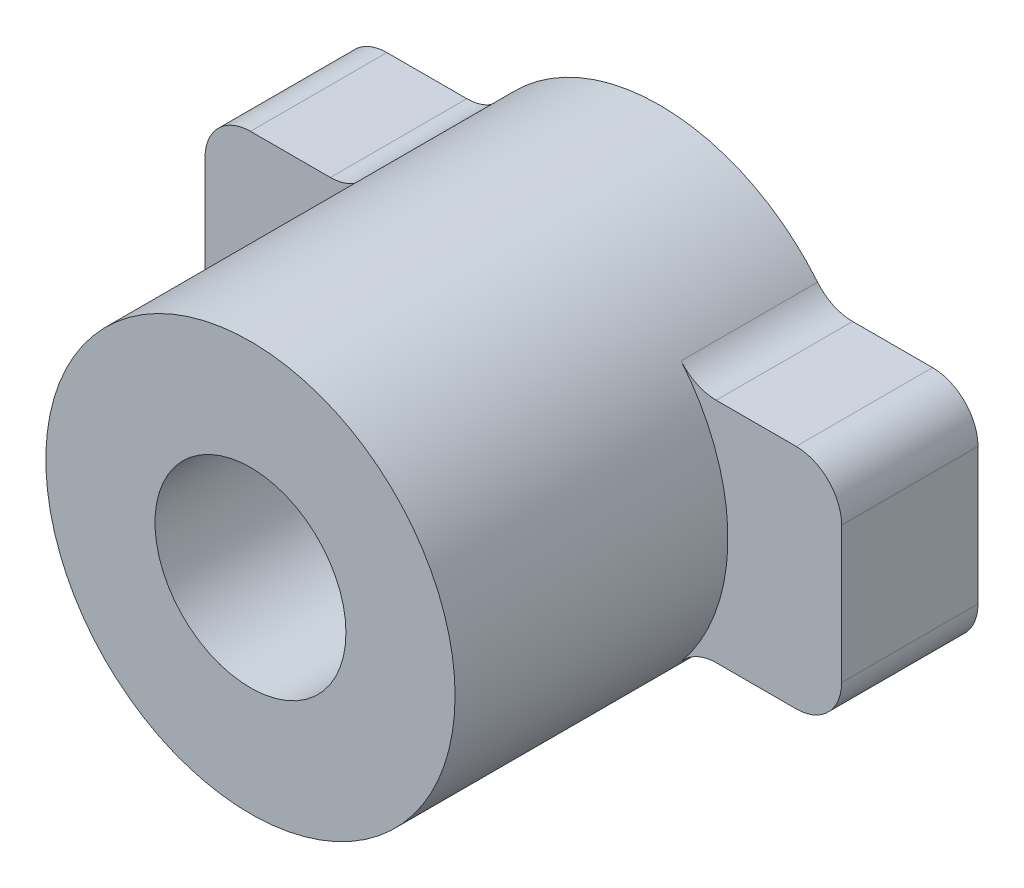
SolidWorks part; units mm, degrees
material "6061 合金"
ref_plane "前视基准面" through (0, 0, 0) normal (0, 0, 1) x (1, 0, 0)
ref_plane "上视基准面" through (0, 0, 0) normal (0, 1, 0) x (1, 0, 0)
ref_plane "右视基准面" through (0, 0, 0) normal (1, 0, 0) x (0, 0, -1)
sketch "草图1" plane through (0, 0, 0) normal (0, 0, 1) x (1, 0, 0)
  circle A0 centre (0, 0) radius 4.5
  dimension "D1" = 9
extrude "凸台-拉伸1" add sketch "草图1" along normal blind 9
sketch "草图2" plane through (0, 0, 0) normal (0, 0, -1) x (-1, 0, 0)
  line L1 (-7, -2.5) -> (7, -2.5)
  line L2 (-7, -2.5) -> (-7, 2.5)
  line L3 (-7, 2.5) -> (7, 2.5)
  line L4 (7, -2.5) -> (7, 2.5)
  line L5 (0, 2.5) -> (0, -2.5) construction
  line L6 (-7, 0) -> (7, 0) construction
  point P0 (0, 0)
  dimension "D1" = 14
  dimension "D2" = 5
extrude "凸台-拉伸2" add sketch "草图2" against normal blind 3
hole_wizard "M5 螺纹孔1" positions "草图3" profile "草图4" tap size "M5" standard "GB" end condition up to next
sketch "草图3" plane through (0, 0, 9) normal (0, 0, 1) x (1, 0, 0)
  point P0 (0, 0)
sketch "草图4" plane through (0, 0, 9) normal (1, 0, 0) x (0, -1, 0)
  line L0 (0, 0) -> (0, 9)
  line L1 (0, 9) -> (2.1, 9)
  line L2 (2.1, 9) -> (2.1, 0)
  line L5 (2.1, 0) -> (0, 0)
  line L11 (0, -6.35) -> (0, 107.95) construction
  dimension "通孔螺纹孔钻头直径" = 4.2
  dimension "通孔螺纹孔钻头深度" = 9
cosmetic thread "孔螺蚊线1"
fillet "圆角1" radius 1 8 edges at (3.7417, 2.5, 1.5) (-3.7417, 2.5, 1.5) (-7, 2.5, 1.5) (-7, -2.5, 1.5) (-3.7417, -2.5, 1.5) (3.7417, -2.5, 1.5) (7, 2.5, 1.5) (7, -2.5, 1.5)
